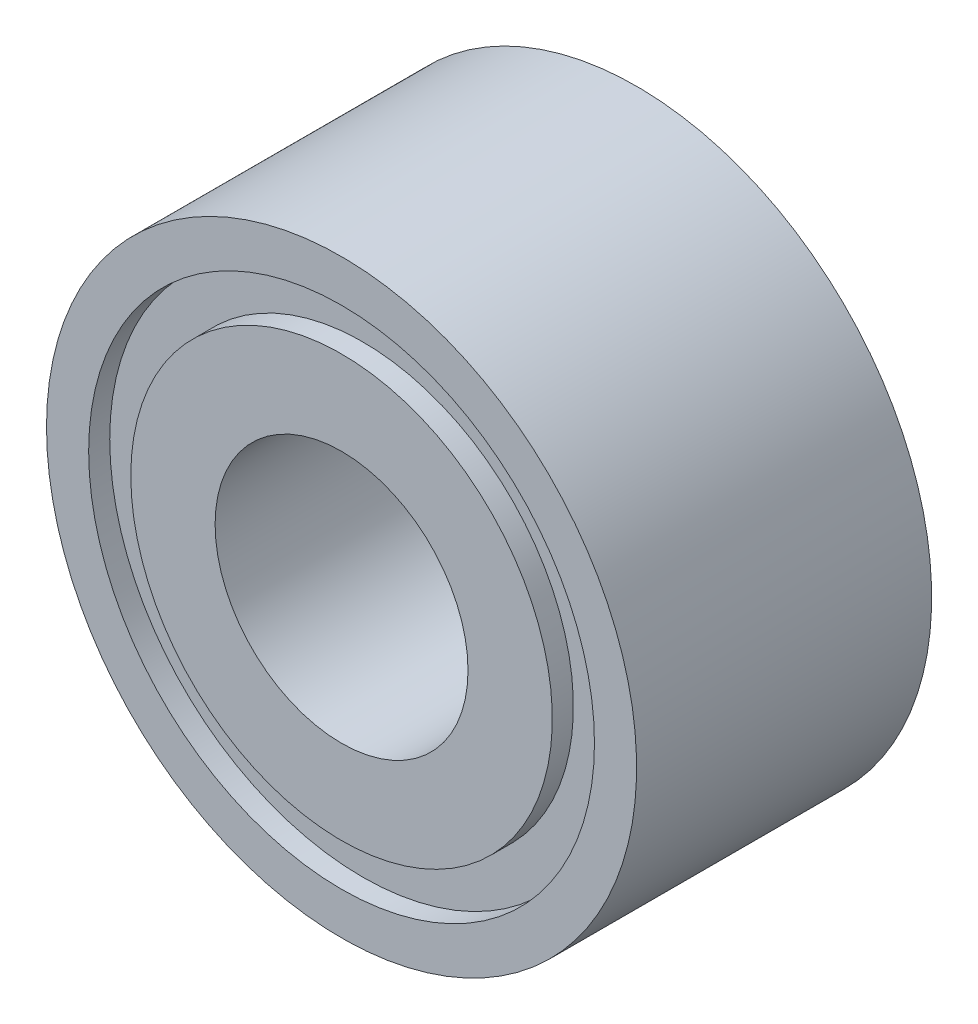
SolidWorks part; units mm, degrees
material "镀铬不锈钢"
ref_plane "前视基准面" through (0, 0, 0) normal (0, 0, 1) x (1, 0, 0)
ref_plane "上视基准面" through (0, 0, 0) normal (0, 1, 0) x (1, 0, 0)
ref_plane "右视基准面" through (0, 0, 0) normal (1, 0, 0) x (0, 0, -1)
sketch "草图1" plane through (0, 0, 0) normal (0, 1, 0) x (1, 0, 0)
  line L7 (0, 0) -> (-7, 0) construction
  line L13 (-7, -3.5) -> (-7, 3.5)
  line L14 (-7, 3.5) -> (-6, 3.5)
  line L15 (-6, 3.5) -> (-6, 3)
  line L16 (-6, 3) -> (-5, 3)
  line L17 (-5, 3) -> (-5, 3.5)
  line L18 (-5, 3.5) -> (-3, 3.5)
  line L19 (-3, 3.5) -> (-3, -3.5)
  line L20 (-5, -3.5) -> (-3, -3.5)
  line L21 (-5, -3) -> (-5, -3.5)
  line L22 (-6, -3) -> (-5, -3)
  line L23 (-6, -3.5) -> (-6, -3)
  line L24 (-7, -3.5) -> (-6, -3.5)
  line L25 (0, 0) -> (0, -4.3153) construction
  point P11 (-3, 0)
  dimension "D1" = 3
  dimension "D2" = 7
  dimension "D3" = 4
  dimension "D4" = 1
  dimension "D5" = 2
  dimension "D6" = 0.5
revolve "旋转1" add sketch "草图1" angle 360 about L25
